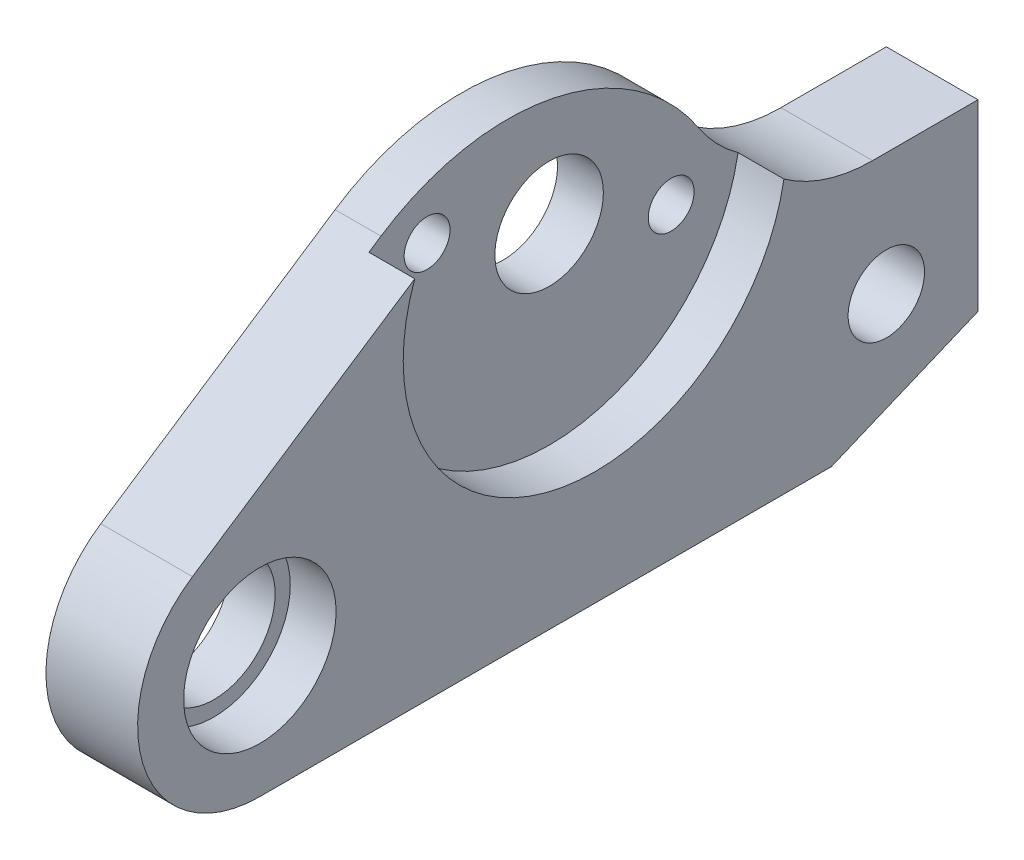
SolidWorks part; units mm, degrees
ref_plane "Front Plane" through (0, 0, 0) normal (0, 0, 1) x (1, 0, 0)
ref_plane "Top Plane" through (0, 0, 0) normal (0, 1, 0) x (1, 0, 0)
ref_plane "Right Plane" through (0, 0, 0) normal (1, 0, 0) x (0, 0, -1)
sketch "Sketch1" plane through (0, 0, 0) normal (1, 0, 0) x (0, 0, -1)
  line L0 (-4.4103, 6.6745) -> (10.925, 16.8075)
  line L1 (37.4, -8) -> (47, -4)
  line L2 (47, -4) -> (47, 8)
  line L3 (29.9191, 9.0928) -> (13.9443, 14.9072) construction
  line L4 (47, 8) -> (40.1015, 8)
  line L5 (37.4, -8) -> (0, -8)
  line L6 (-9, -42) -> (51, -42) construction
  line L7 (-9, -42) -> (-9, 16) construction
  line L8 (-9, 16) -> (51, 16) construction
  line L9 (51, -42) -> (51, 16) construction
  arc A0 (-4.4103, 6.6745) -> (0, -8) centre (0, 0) ccw
  circle A1 centre (21.9317, 12) radius 12.5 construction
  arc A2 (31.7386, 12.5171) -> (10.925, 16.8075) centre (19.1943, 4.2928) ccw
  circle A3 centre (21.9317, 12) radius 3.55
  circle A4 centre (41, 0) radius 6 construction
  circle A5 centre (0, 0) radius 4
  circle A6 centre (41, 0) radius 2.5
  circle A7 centre (29.9191, 9.0928) radius 1.5
  circle A8 centre (13.9443, 14.9072) radius 1.5
  circle A9 centre (29.9191, 9.0928) radius 3.25 construction
  circle A10 centre (13.9443, 14.9072) radius 3.25 construction
  arc A11 (40.1015, 8) -> (31.7386, 12.5171) centre (40.1015, 18) cw
  dimension "D5" = 5
  dimension "D6" = 8
  dimension "D7" = 8
  dimension "D8" = 25
  dimension "D10" = 7.1
  dimension "D14" = 15
  dimension "D15" = 3
  dimension "D17" = 6.5
  dimension "D18" = 10
  dimension "D20" = 12
  dimension "D1" = 60
  dimension "D2" = 58
  dimension "D3" = 42
  dimension "D4" = 9
  dimension "D9" = 12
  dimension "D11" = 25
  dimension "D12" = 42
  dimension "D13" = 50
  dimension "D16" = 8.5
  dimension "D19" = 20
  dimension "D21" = 12
  dimension "D23" = 8
extrude "Boss-Extrude1" add sketch "Sketch1" along normal blind 6
sketch "Sketch2" plane through (6, 0, 0) normal (1, 0, 0) x (0, 0, -1)
  circle A0 centre (0, 0) radius 4.99
  dimension "D1" = 9.98
extrude "Cut-Extrude1" cut sketch "Sketch2" against normal blind 3
sketch "Sketch3" plane through (6, 0, 0) normal (1, 0, 0) x (0, 0, -1)
  circle A0 centre (21.9317, 12) radius 12.55
  dimension "D1" = 25.1
extrude "Cut-Extrude2" cut sketch "Sketch3" against normal blind 3
